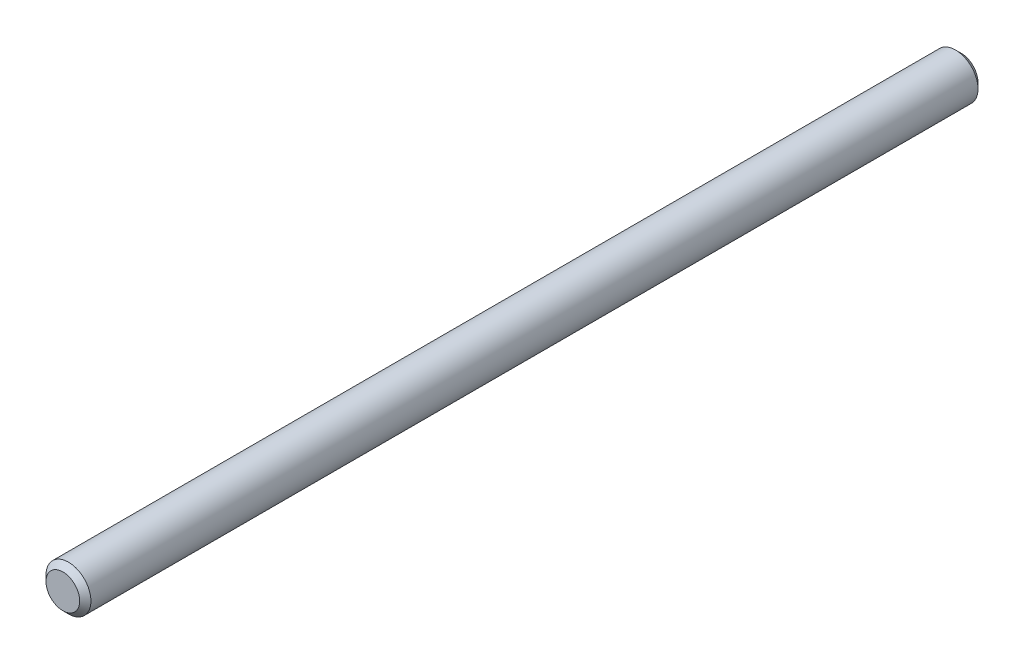
SolidWorks part; units mm, degrees
material "Acier non allié"
ref_plane "Front Plane" through (0, 0, 0) normal (0, 0, 1) x (1, 0, 0)
ref_plane "Top Plane" through (0, 0, 0) normal (0, 1, 0) x (1, 0, 0)
ref_plane "Right Plane" through (0, 0, 0) normal (1, 0, 0) x (0, 0, -1)
sketch "Sketch1" plane through (0, 0, 0) normal (0, 0, 1) x (1, 0, 0)
  circle A0 centre (0, 0) radius 4
  dimension "D1" = 8
extrude "Boss-Extrude1" add sketch "Sketch1" along normal blind 160
chamfer "Chamfer1" distance 1 angle 45 2 edges at (4, 0, 160) (4, 0, 0)
equation "\"L\"= 160"
equation "\"D1@Boss-Extrude1\"=\"L\""
